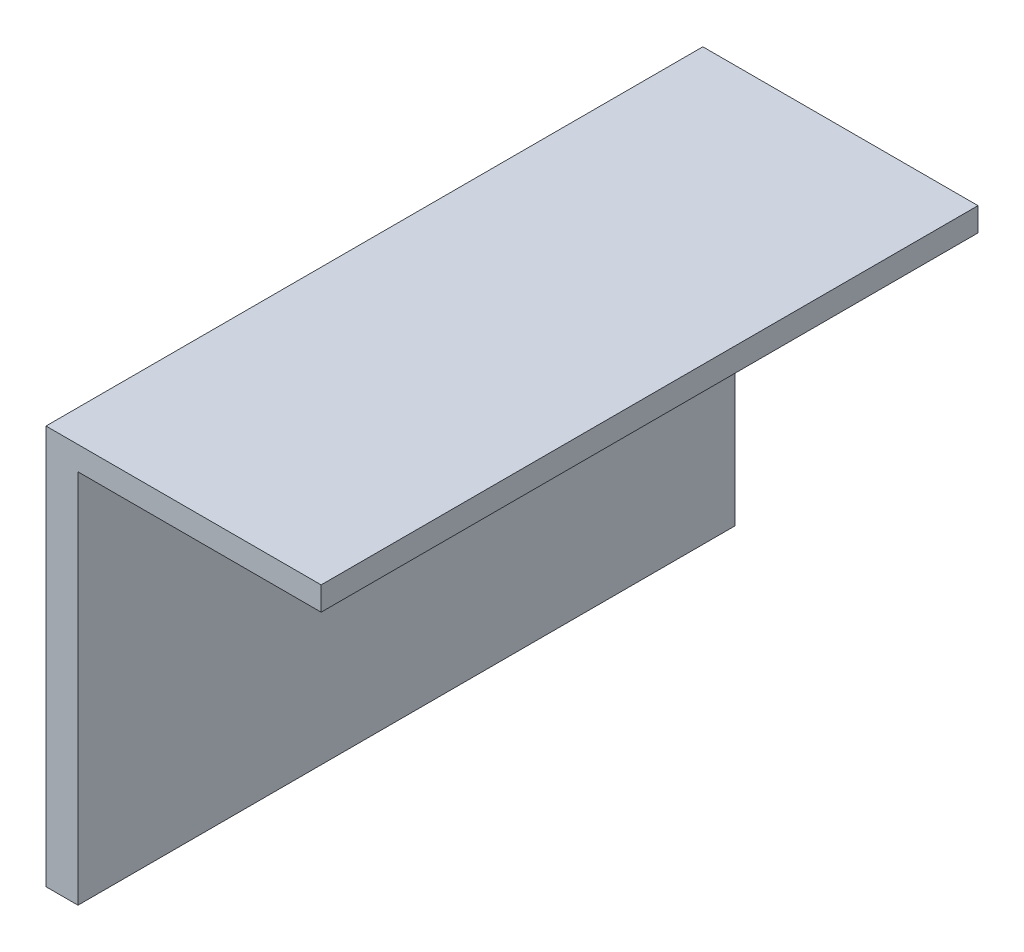
SolidWorks part; units mm, degrees
ref_plane "Front Plane" through (0, 0, 0) normal (0, 0, 1) x (1, 0, 0)
ref_plane "Top Plane" through (0, 0, 0) normal (0, 1, 0) x (1, 0, 0)
ref_plane "Right Plane" through (0, 0, 0) normal (1, 0, 0) x (0, 0, -1)
sketch "Sketch1" plane through (0, 0, 0) normal (1, 0, 0) x (0, 0, -1)
  line L0 (-138.9521, 18.3793) -> (71.0479, 18.3793) construction
  line L1 (2.1225, -13.2993) -> (-50.0268, -13.2993)
  line L2 (2.1225, -13.2993) -> (2.1225, 18.3793)
  line L3 (2.1225, 18.3793) -> (-50.0268, 18.3793)
  line L4 (-50.0268, -13.2993) -> (-50.0268, 18.3793)
  line L5 (2.1225, -13.2993) -> (-50.0268, 18.3793) construction
  line L6 (2.1225, 18.3793) -> (-50.0268, -13.2993) construction
  point P0 (-23.9521, 2.54)
  point P5 (0, 0)
  point P6 (2.0765, 13.407)
extrude "Boss-Extrude1" add sketch "Sketch1" along normal blind 2.54
sketch "Sketch2" plane through (2.54, 0, 0) normal (1, 0, 0) x (0, 0, -1)
  line L0 (-138.9521, 18.3793) -> (71.0479, 18.3793) construction
  line L1 (-50.0268, 18.3793) -> (2.1225, 18.3793)
  line L2 (-50.0268, 18.3793) -> (-50.0268, 16.5012)
  line L3 (-50.0268, 16.5012) -> (2.1225, 16.5012)
  line L4 (2.1225, 18.3793) -> (2.1225, 16.5012)
  line L5 (-50.0268, 18.3793) -> (-50.0268, -13.2993) construction
  line L6 (2.1225, -13.2993) -> (2.1225, 18.3793) construction
extrude "Boss-Extrude2" add sketch "Sketch2" along normal blind 19.304
